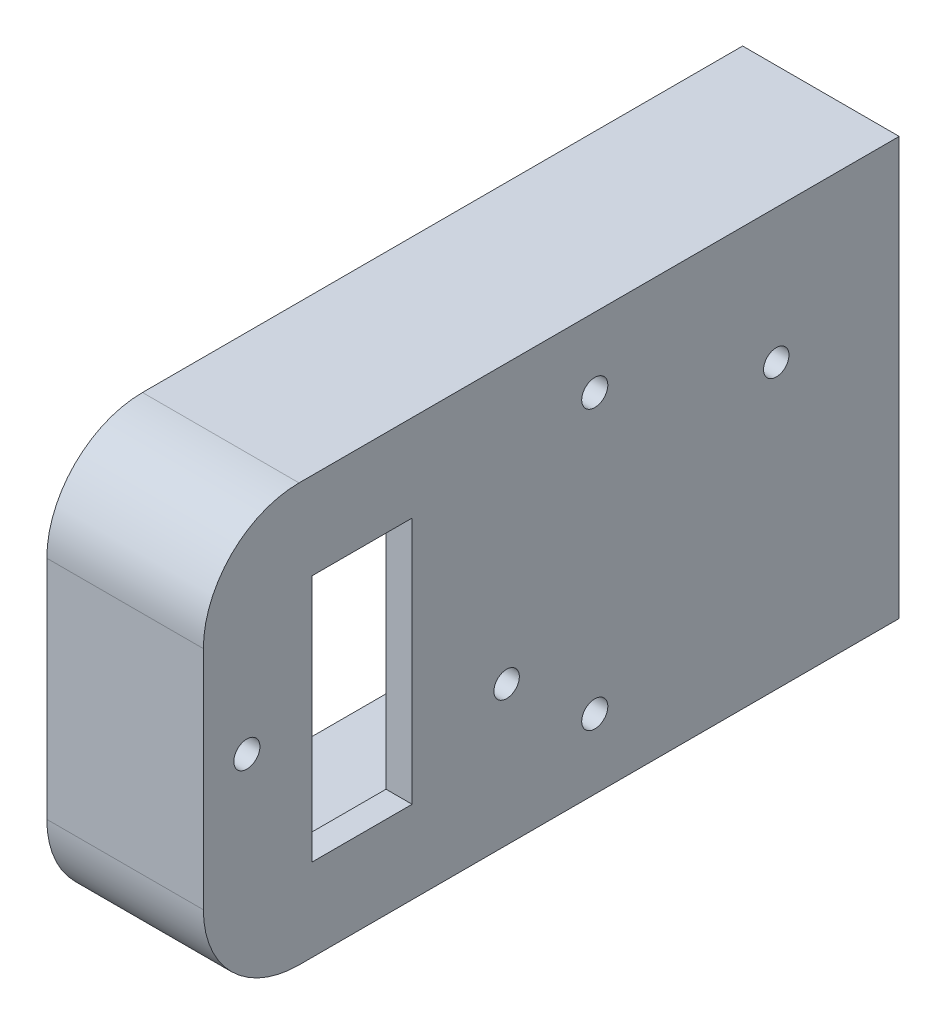
SolidWorks part; units mm, degrees
ref_plane "Plano frontal" through (0, 0, 0) normal (1, 0, 0) x (0, 1, 0)
ref_plane "Plano superior" through (0, 0, 0) normal (0, 0, 1) x (0, 1, 0)
ref_plane "Plano direito" through (0, 0, 0) normal (0, 1, 0) x (-1, 0, 0)
sketch "Esboço1" plane through (0, 0, 0) normal (1, 0, 0) x (0, 1, 0)
  line L1 (-13, 40) -> (13, 40)
  line L2 (-24, 29) -> (-24, -40)
  line L3 (-24, -40) -> (24, -40)
  line L4 (24, 29) -> (24, -40)
  line L5 (-24, 40) -> (24, -40) construction
  line L6 (-24, -40) -> (24, 40) construction
  arc A1 (-13, 40) -> (-24, 29) centre (-13, 29) ccw
  arc A2 (13, 40) -> (24, 29) centre (13, 29) cw
  point P0 (0, 0)
  point P8 (0, 0)
  dimension "D3" = 11
  dimension "D1" = 80
  dimension "D2" = 48
extrude "Ressalto-extrusão2" add sketch "Esboço1" along normal blind 3
sketch "Esboço2" plane through (0, 0, 0) normal (-1, 0, 0) x (0, -1, 0)
  line L5 (-13, 40) -> (13, 40) construction
  line L10 (-20, -37) -> (20, -37)
  line L11 (-20, -37) -> (-20, 26)
  line L13 (-9, 37) -> (9, 37)
  line L14 (20, -37) -> (20, 26)
  line L15 (-13, 40) -> (13, 40)
  line L16 (-24, 29) -> (-24, -40)
  line L17 (-24, -40) -> (24, -40)
  line L18 (24, 29) -> (24, -40)
  line L19 (-24, -40) -> (-24, 29) construction
  arc A0 (-13, 40) -> (-24, 29) centre (-13, 29) ccw
  arc A1 (13, 40) -> (24, 29) centre (13, 29) cw
  arc A2 (9, 37) -> (20, 26) centre (9, 26) cw
  arc A3 (-20, 26) -> (-9, 37) centre (-9, 26) cw
  point P9 (0, 0)
  dimension "D4" = 11
  dimension "D5" = 11
  dimension "D1" = 4
  dimension "D2" = 4
  dimension "D3" = 3
  dimension "D6" = 3
extrude "Ressalto-extrusão3" add sketch "Esboço2" along normal blind 15
sketch "Esboço3" plane through (3, 0, 0) normal (1, 0, 0) x (0, 1, 0)
  circle A0 centre (0, 35) radius 1.5
  circle A1 centre (16, -5) radius 1.5
  circle A2 centre (-16, -5) radius 1.5
extrude "Corte-extrusão1" cut sketch "Esboço3" against normal through all
sketch "Esboço4" plane through (0, 0, 0) normal (-1, 0, 0) x (0, -1, 0)
  circle A0 centre (7.9489, 5.1339) radius 1.4605
  circle A1 centre (-8.5738, -25.8659) radius 1.4605
extrude "Corte-extrusão2" cut sketch "Esboço4" against normal through all
sketch "Esboço5" plane through (0, 0, 0) normal (-1, 0, 0) x (0, -1, 0)
  line L0 (14.5, 16) -> (14.5, 27.5)
  line L1 (14, 16.5) -> (-13.5, 16.5)
  line L2 (14, 16.5) -> (14, 27)
  line L3 (14, 27) -> (-13.5, 27)
  line L4 (-13.5, 16.5) -> (-13.5, 27)
  line L5 (14.5, 27.5) -> (-14, 27.5)
  line L6 (-14, 16) -> (-14, 27.5)
  line L7 (14.5, 16) -> (-14, 16)
  dimension "D1" = 0.5
extrude "Corte-extrusão3" cut sketch "Esboço5" against normal through all contours L4 L1 L2 L3 | L7 L0 L5 L6 L1 L4 L3 L2
